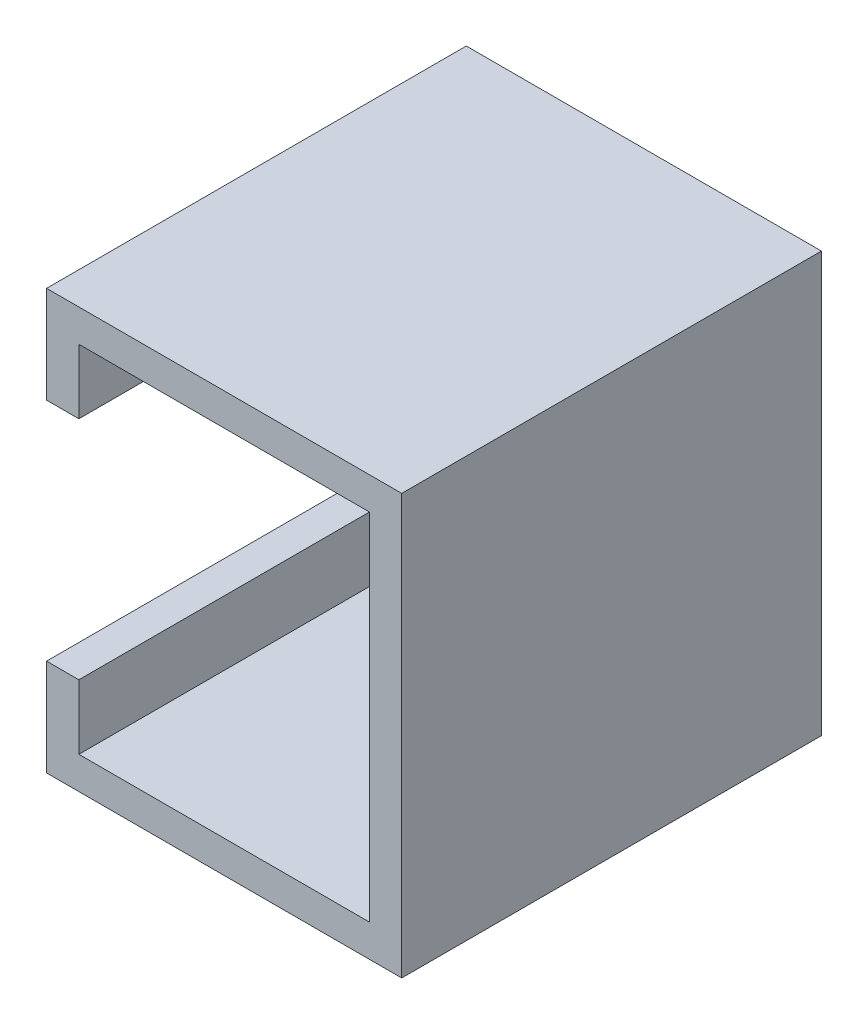
SolidWorks part; units mm, degrees
ref_plane "Ebene vorne" through (0, 0, 0) normal (0, 0, 1) x (1, 0, 0)
ref_plane "Ebene oben" through (0, 0, 0) normal (0, 1, 0) x (1, 0, 0)
ref_plane "Ebene rechts" through (0, 0, 0) normal (1, 0, 0) x (0, 0, -1)
sketch "Skizze1" plane through (0, 0, 0) normal (1, 0, 0) x (0, 0, -1)
  line L1 (0, 0) -> (13, 0)
  line L2 (0, 0) -> (0, 13)
  line L3 (0, 13) -> (13, 13)
  line L4 (13, 0) -> (13, 13)
  dimension "D1" = 13
  dimension "D2" = 13
extrude "Aufsatz-Linear austragen1" add sketch "Skizze1" along normal blind 11
shell "Wandung1" thickness 1
sketch "Skizze2" plane through (0, 0, 0) normal (0, 0, 1) x (1, 0, 0)
  line L0 (0, 13) -> (0, 0) construction
  line L1 (0, 10) -> (1, 10)
  line L2 (0, 10) -> (0, 3)
  line L3 (0, 3) -> (1, 3)
  line L4 (1, 10) -> (1, 3)
  line L5 (1, 12) -> (1, 1) construction
  line L7 (10, 1) -> (1, 1) construction
  dimension "D1" = 7
  dimension "D2" = 2
extrude "Schnitt-Linear austragen1" cut sketch "Skizze2" against normal up to surface (12 mm away) up to face at (5.5, 6.5, -12)
